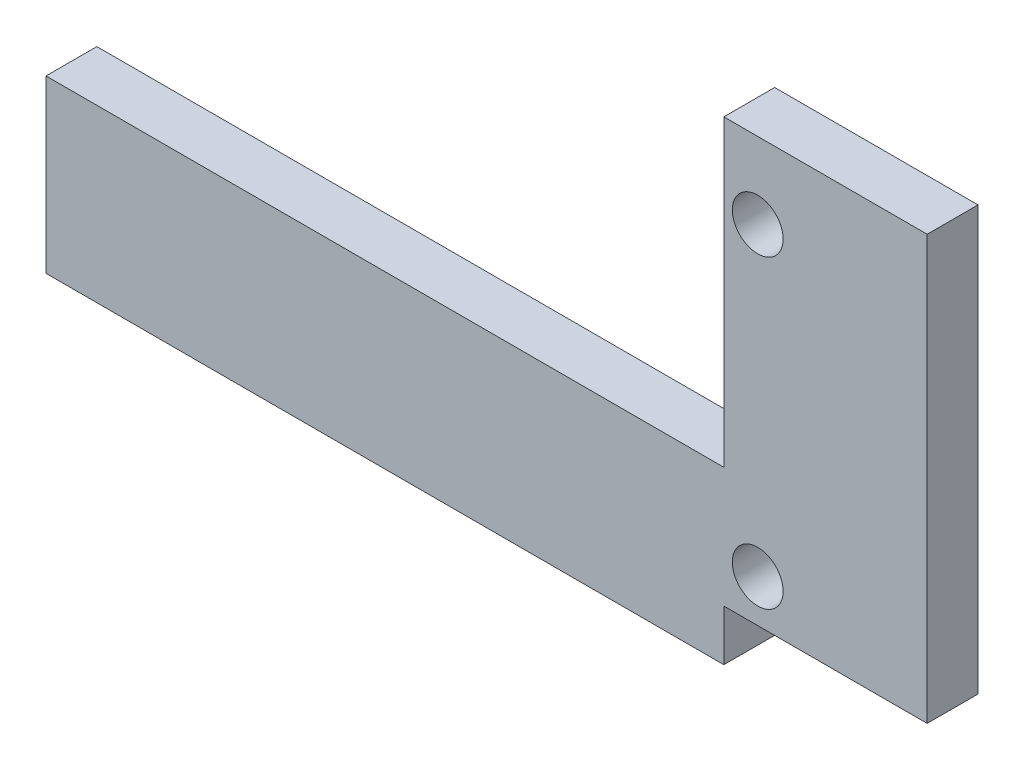
SolidWorks part; units mm, degrees
ref_plane "Front Plane" through (0, 0, 0) normal (0, 0, 1) x (1, 0, 0)
ref_plane "Top Plane" through (0, 0, 0) normal (0, 1, 0) x (1, 0, 0)
ref_plane "Right Plane" through (0, 0, 0) normal (1, 0, 0) x (0, 0, -1)
sketch "Sketch1" plane through (0, 0, 0) normal (0, 0, 1) x (1, 0, 0)
  line L1 (0, 0) -> (-12, 0)
  line L2 (0, 0) -> (0, 25)
  line L3 (0, 25) -> (-12, 25)
  line L4 (-12, 0) -> (-12, 25)
  dimension "D1" = 12
  dimension "D2" = 25
extrude "Boss-Extrude1" add sketch "Sketch1" along normal blind 3
sketch "Sketch2" plane through (0, 0, 0) normal (0, 0, -1) x (-1, 0, 0)
  line L0 (12, 0) -> (0, 0) construction
  line L1 (12, 25) -> (12, 0) construction
  circle A0 centre (10, 2.5) radius 1.5
  circle A1 centre (10, 20.5) radius 1.5
  dimension "D1" = 3
  dimension "D4" = 2
  dimension "D2" = 2.5
  dimension "D3" = 18
extrude "Cut-Extrude2" cut sketch "Sketch2" against normal blind 40
sketch "Sketch4" plane through (-12, 0, 0) normal (-1, 0, 0) x (0, 0, 1)
  line L0 (0, 25) -> (0, 0) construction
  line L1 (0, 11.0902) -> (3, 11.0902)
  line L2 (0, 11.0902) -> (0, -3)
  line L3 (0, -3) -> (3, -3)
  line L4 (3, 11.0902) -> (3, -3)
  dimension "D1" = 0
  dimension "D2" = 3
extrude "Boss-Extrude3" add sketch "Sketch4" along normal blind 40
sketch "Sketch5" plane through (0, 0, 0) normal (0, 0, -1) x (-1, 0, 0)
  line L0 (52, 11.0902) -> (52, -3) construction
  line L1 (12, 11.0902) -> (52, 11.0902)
  line L2 (12, 11.0902) -> (12, 7.0903)
  line L3 (12, 7.0903) -> (52, 7.0903)
  line L4 (52, 11.0902) -> (52, 7.0903)
extrude "Cut-Extrude3" cut sketch "Sketch5" against normal blind 10
